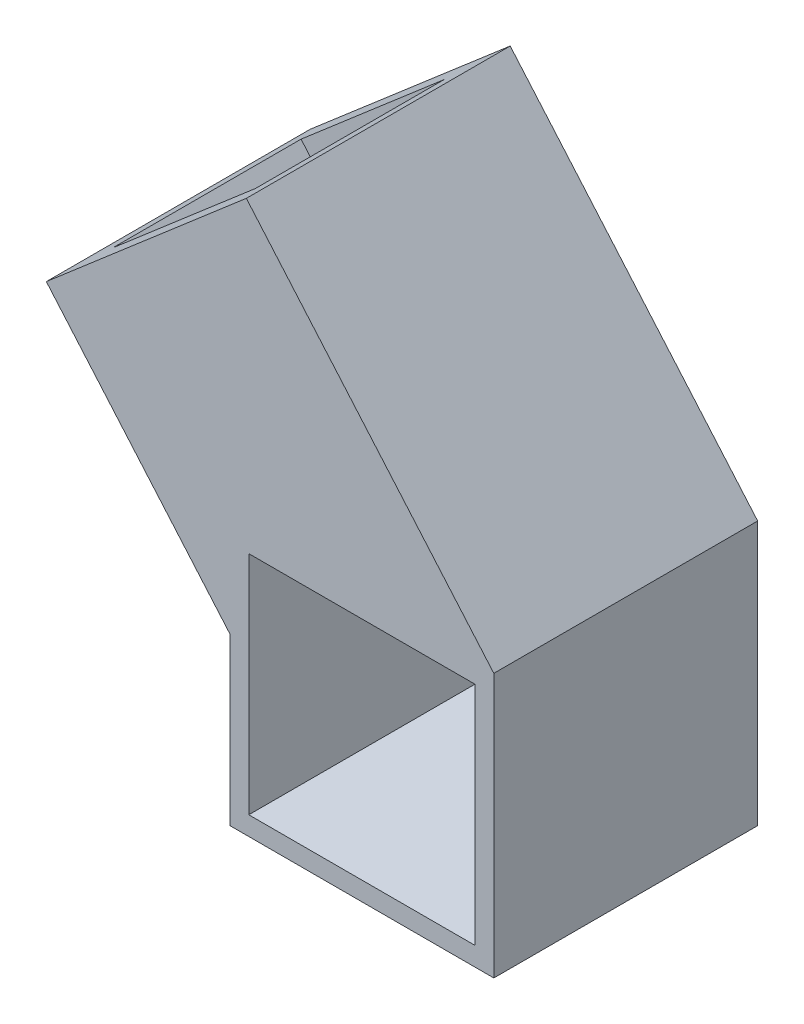
SolidWorks part; units mm, degrees
ref_plane "前视基准面" through (0, 0, 0) normal (0, 0, 1) x (1, 0, 0)
ref_plane "上视基准面" through (0, 0, 0) normal (0, 1, 0) x (1, 0, 0)
ref_plane "右视基准面" through (0, 0, 0) normal (1, 0, 0) x (0, 0, -1)
sketch "草图1" plane through (0, 0, 0) normal (0, 0, 1) x (1, 0, 0)
  line L1 (0, 0) -> (14, 0)
  line L2 (0, 0) -> (0, 14)
  line L3 (0, 14) -> (14, 14)
  line L4 (14, 0) -> (14, 14)
  line L6 (1, 1) -> (13, 1)
  line L7 (1, 1) -> (1, 13)
  line L8 (1, 13) -> (13, 13)
  line L9 (13, 1) -> (13, 13)
extrude "凸台-拉伸1" add sketch "草图1" along normal blind 14
sketch "草图2" plane through (0, 0, 0) normal (0, 0, -1) x (-1, 0, 0)
  line L0 (0, 14) -> (0, 0) construction
  line L1 (-8.0441, 20.9217) -> (0, 14)
  line L2 (-8.0441, 20.9217) -> (2.568, 11.7903)
  line L3 (2.568, 11.7903) -> (0, 8.8058)
  line L4 (0, 8.8058) -> (-14, 14)
  line L5 (-14, 14) -> (0, 14) construction
  line L6 (-14, 14) -> (-8.0441, 20.9217)
  line L7 (2.568, 11.7903) -> (9.7427, 20.1284)
  line L8 (9.7427, 20.1284) -> (-0.8695, 29.2598)
  line L9 (-0.8695, 29.2598) -> (-8.0441, 20.9217)
  point P0 (0, 8.8058)
  point P1 (-8.0441, 20.9217)
  line M2 (0, 0) -> (0, 14)
  line M3 (0, 14) -> (-14, 14)
extrude "凸台-拉伸3" add sketch "草图2" against normal blind 14 contours L8 L9 L1 L2 L7 | L6 L1 M3 | L3 L2 M2
sketch "草图3" plane through (-14.0964, 16.3822, 0) normal (-0.6522, 0.758, 0) x (0.758, 0.6522, 0)
  line L0 (5.7435, 0) -> (5.7435, -2)
  line L1 (5.7435, -14) -> (5.7435, 0) construction
  line L3 (7.7435, -2) -> (17.7435, -2)
  line L4 (17.7435, -2) -> (17.7435, -12)
  line L5 (17.7435, -12) -> (7.7435, -12)
  line L6 (7.7435, -12) -> (7.7435, -2)
  point P0 (5.7435, 0)
extrude "切除-拉伸1" cut sketch "草图3" against normal blind 10 contours L6 L5 L4 L3
